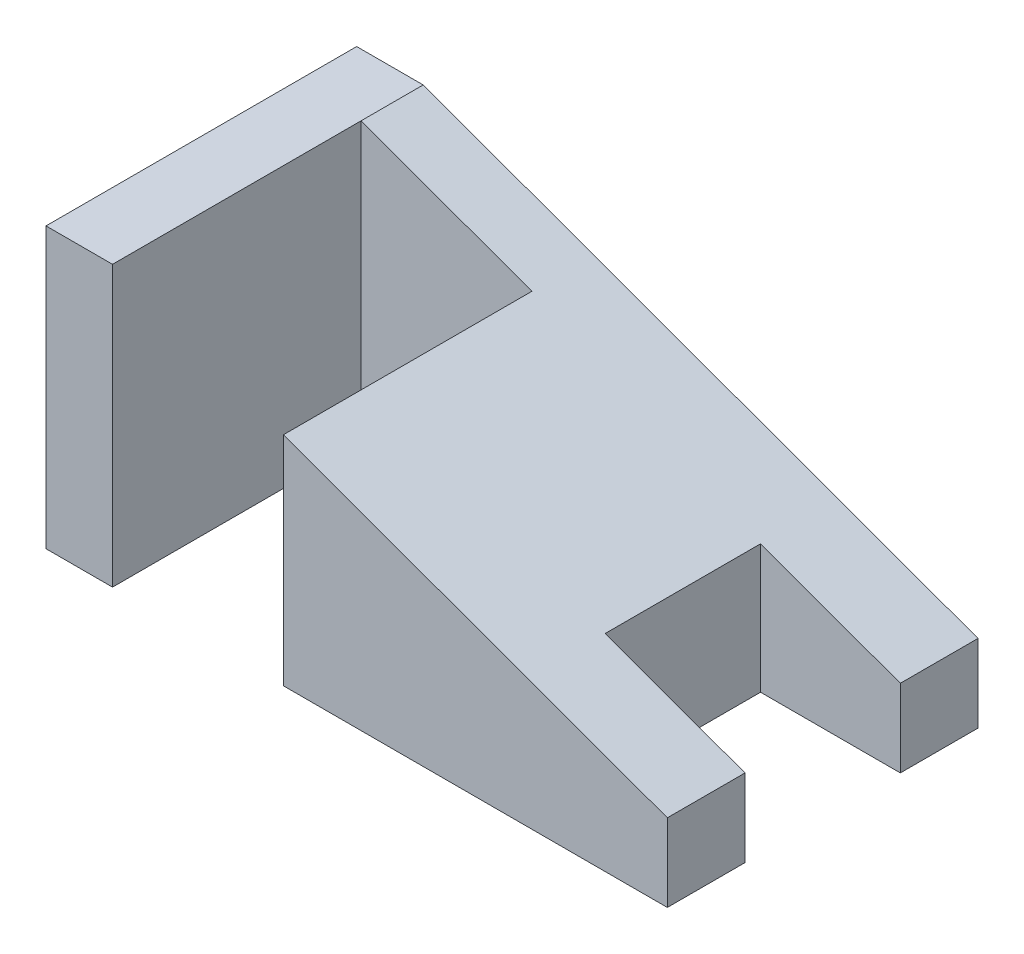
SolidWorks part; units mm, degrees
ref_plane "Front Plane" through (0, 0, 0) normal (0, 0, 1) x (1, 0, 0)
ref_plane "Top Plane" through (0, 0, 0) normal (0, 1, 0) x (1, 0, 0)
ref_plane "Right Plane" through (0, 0, 0) normal (1, 0, 0) x (0, 0, -1)
sketch "Sketch1" plane through (0, 0, 0) normal (0, 0, 1) x (1, 0, 0)
  line L0 (0, 0) -> (200, 0)
  line L1 (200, 0) -> (200, 25)
  line L2 (200, 25) -> (21.414, 90)
  line L3 (21.414, 90) -> (0, 90)
  line L4 (0, 90) -> (0, 0)
  dimension "D1" = 200
  dimension "D2" = 20
  dimension "D3" = 25
  dimension "D4" = 90
extrude "Boss-Extrude1" add sketch "Sketch1" along normal blind 100
sketch "Sketch2" plane through (0, 90, 0) normal (0, 1, 0) x (1, 0, 0)
  line L0 (21.414, -20) -> (76.414, -20)
  line L1 (21.414, -100) -> (21.414, 0) construction
  line L2 (76.414, -20) -> (76.414, -100)
  line L3 (200, -100) -> (21.414, -100) construction
  line L4 (200, -25) -> (155, -25)
  line L5 (200, -100) -> (200, 0) construction
  line L6 (155, -25) -> (155, -75)
  line L7 (155, -75) -> (200, -75)
  line L8 (200, 0) -> (21.414, 0) construction
  line L9 (76.414, -100) -> (21.414, -100)
  line L10 (21.414, -100) -> (21.414, -20)
  line L11 (200, -25) -> (200, -75)
  dimension "D1" = 50
  dimension "D2" = 45
  dimension "D3" = 55
  dimension "D4" = 80
  dimension "D5" = 25
extrude "Cut-Extrude1" cut sketch "Sketch2" against normal up to next
